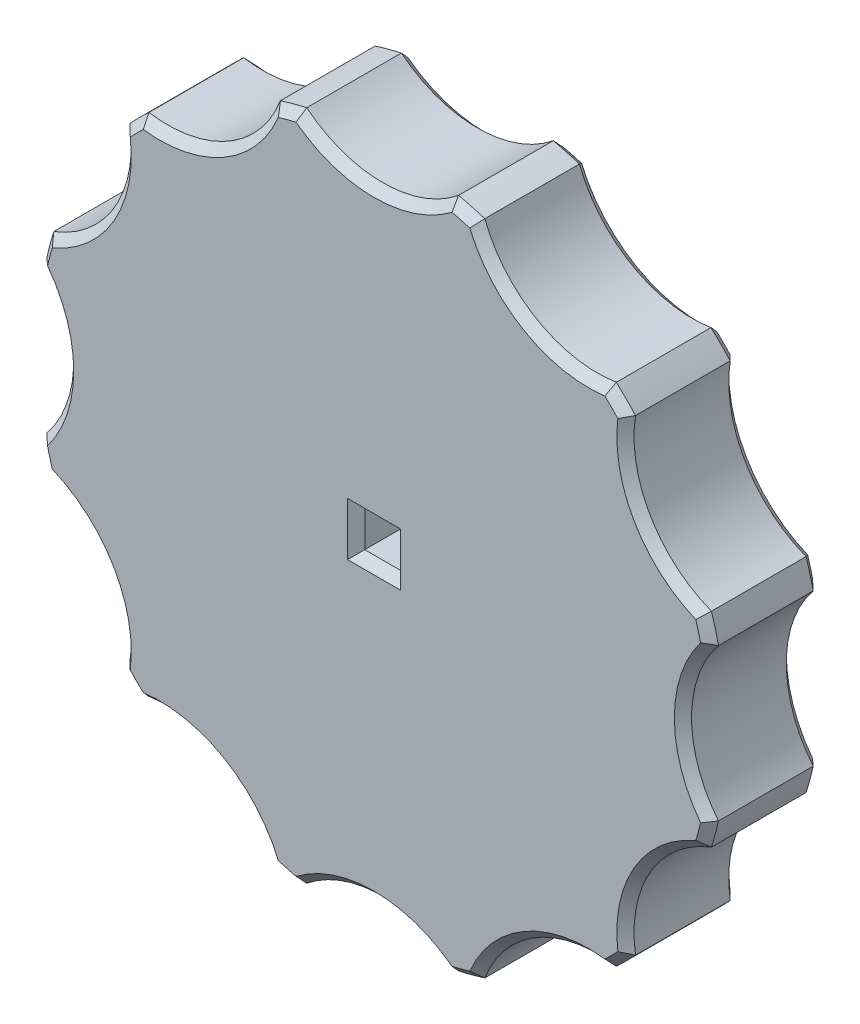
SolidWorks part; units mm, degrees
ref_plane "Ebene vorne" through (0, 0, 0) normal (0, 0, 1) x (1, 0, 0)
ref_plane "Ebene oben" through (0, 0, 0) normal (0, 1, 0) x (1, 0, 0)
ref_plane "Ebene rechts" through (0, 0, 0) normal (1, 0, 0) x (0, 0, -1)
sketch "Skizze1" plane through (0, 0, 0) normal (0, 0, 1) x (1, 0, 0)
  line L1 (1.04, -1.04) -> (-1.04, -1.04)
  line L2 (1.04, -1.04) -> (1.04, 1.04)
  line L3 (1.04, 1.04) -> (-1.04, 1.04)
  line L4 (-1.04, -1.04) -> (-1.04, 1.04)
  line L5 (1.04, -1.04) -> (-1.04, 1.04) construction
  line L6 (1.04, 1.04) -> (-1.04, -1.04) construction
  circle A0 centre (0, 0) radius 20
  dimension "D1" = 40
  dimension "D2" = 2.08
  dimension "D3" = 2.08
extrude "Aufsatz-Linear austragen1" add sketch "Skizze1" along normal blind 6.5
sketch "Skizze2" plane through (0, 0, 0) normal (0, 0, 1) x (1, 0, 0)
  line L0 (-5.5355, 20.6588) -> (5.5355, 20.6588)
  line L1 (0, 0) -> (-5.5355, 20.6588) construction
  line L2 (0, 0) -> (5.5355, 20.6588) construction
  arc A0 (-5.5355, 20.6588) -> (5.5355, 20.6588) centre (0, 24.9435) ccw
  dimension "D1" = 7
  dimension "D2" = 30
extrude "Schnitt-Linear austragen1" cut sketch "Skizze2" along normal blind 6.5
pattern_circular "Kreismuster1" count 12 every 30 about axis through (0, 0, 0) along (0, 0, 1) of "Schnitt-Linear austragen1"
chamfer "Fase1" distance 0.5 angle 45 56 edges at (1.04, 0, 6.5) (0, 1.04, 6.5) (-1.04, 0, 6.5) (0, -1.04, 6.5) (17.9435, 0, 6.5) (14.1421, -14.1421, 6.5) (19.3185, -5.1764, 6.5) (15.5395, -8.9717, 6.5) (5.1764, -19.3185, 6.5) (8.9717, -15.5395, 6.5) (-5.1764, -19.3185, 6.5) (0, -17.9435, 6.5) (-14.1421, -14.1421, 6.5) (-8.9717, -15.5395, 6.5) (-19.3185, -5.1764, 6.5) (-15.5395, -8.9717, 6.5) (-19.3185, 5.1764, 6.5) (-17.9435, 0, 6.5) (-14.1421, 14.1421, 6.5) (-15.5395, 8.9717, 6.5) (-5.1764, 19.3185, 6.5) (-8.9717, 15.5395, 6.5) (0, 17.9435, 6.5) (14.1421, 14.1421, 6.5) (5.1764, 19.3185, 6.5) (8.9717, 15.5395, 6.5) (19.3185, 5.1764, 6.5) (15.5395, 8.9717, 6.5) (0, 1.04, 0) (1.04, 0, 0) (0, -1.04, 0) (-1.04, 0, 0) (19.3185, 5.1764, 0) (14.1421, 14.1421, 0) (8.9717, 15.5395, 0) (5.1764, 19.3185, 0) (0, 17.9435, 0) (-5.1764, 19.3185, 0) (-8.9717, 15.5395, 0) (-14.1421, 14.1421, 0) (-15.5395, 8.9717, 0) (-19.3185, 5.1764, 0) (-17.9435, 0, 0) (-19.3185, -5.1764, 0) (-15.5395, -8.9717, 0) (-14.1421, -14.1421, 0) (-8.9717, -15.5395, 0) (-5.1764, -19.3185, 0) (0, -17.9435, 0) (5.1764, -19.3185, 0) (8.9717, -15.5395, 0) (14.1421, -14.1421, 0) (15.5395, -8.9717, 0) (19.3185, -5.1764, 0) (17.9435, 0, 0) (15.5395, 8.9717, 0)
other "Körper speichern1"
